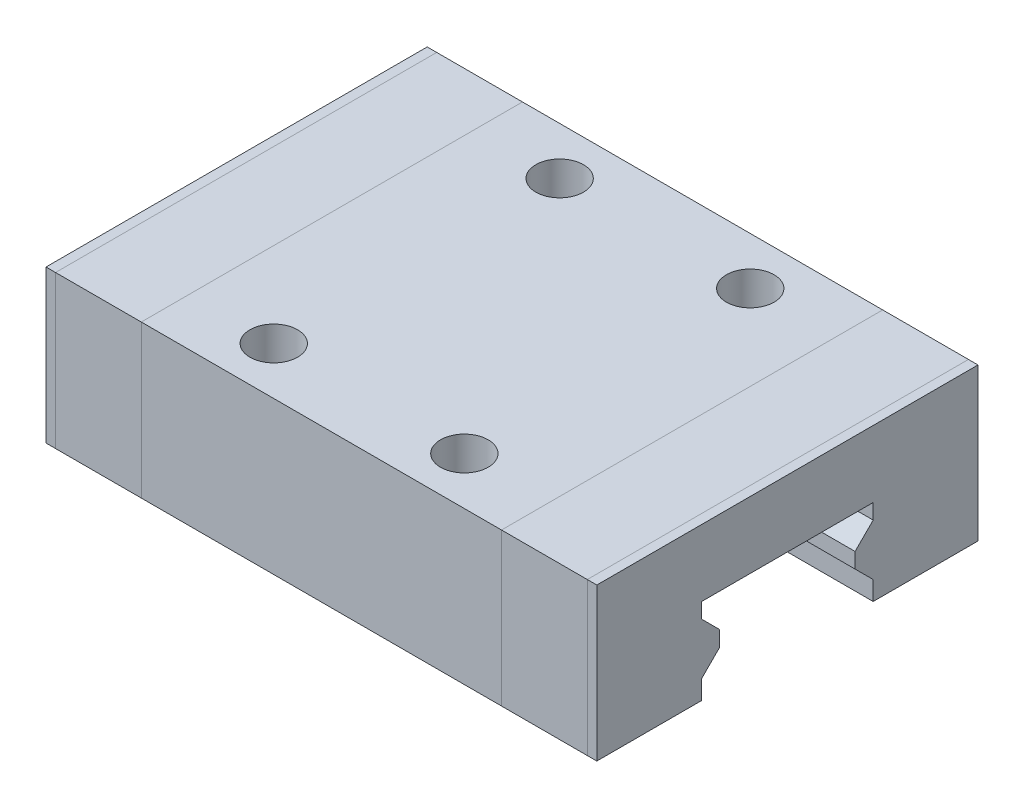
SolidWorks part; units mm, degrees
material "AISI 类型 316L 不锈钢"
ref_plane "前视" through (0, 0, 0) normal (0, 0, 1) x (1, 0, 0)
ref_plane "上视" through (0, 0, 0) normal (0, 1, 0) x (1, 0, 0)
ref_plane "右视" through (0, 0, 0) normal (1, 0, 0) x (0, 0, -1)
sketch "草图1" plane through (0, 0, 0) normal (0, 1, 0) x (1, 0, 0)
  line L1 (14.45, -10) -> (-14.45, -10)
  line L2 (14.45, -10) -> (14.45, 10)
  line L3 (14.45, 10) -> (-14.45, 10)
  line L4 (-14.45, -10) -> (-14.45, 10)
  line L5 (14.45, -10) -> (-14.45, 10) construction
  line L6 (14.45, 10) -> (-14.45, -10) construction
  point P0 (0, 0)
  dimension "D1" = 28.9
  dimension "D2" = 20
extrude "凸台-拉伸1" add sketch "草图1" along normal blind 8
sketch "草图3" plane through (0, 8, 0) normal (0, 1, 0) x (1, 0, 0)
  line L0 (-9.45, 10) -> (-9.45, -10)
  line L1 (14.45, 10) -> (-14.45, 10) construction
  line L2 (-14.45, -10) -> (14.45, -10) construction
  line L3 (9.45, -10) -> (9.45, 10)
  line L4 (0, 0) -> (0, 5.4273) construction
  line L5 (-13.95, 10) -> (-13.95, -10)
  line L6 (13.95, 10) -> (13.95, -10)
  line L7 (-14.45, 10) -> (-14.45, -10) construction
  dimension "D1" = 18.9
  dimension "D2" = 0.5
split line "分割线1"
sketch "草图2" plane through (-14.45, 0, 0) normal (-1, 0, 0) x (0, 0, 1)
  line L0 (-10, 8) -> (10, 8) construction
  line L17 (0, 0) -> (0, 4.5) construction
  line L18 (-4.5, 0) -> (-4.5, 1)
  line L19 (-4.5, 1) -> (-3.55, 1.95)
  line L20 (-3.55, 2.75) -> (-4.5, 3.7)
  line L21 (-4.5, 3.7) -> (-4.5, 4.5)
  line L22 (-4.5, 4.5) -> (4.5, 4.5)
  line L23 (4.5, 3.7) -> (4.5, 4.5)
  line L24 (3.55, 2.75) -> (3.55, 1.95)
  line L25 (3.55, 2.75) -> (4.5, 3.7)
  line L26 (4.5, 0) -> (4.5, 1)
  line L27 (-4.5, 0) -> (4.5, 0)
  line L28 (-3.55, 2.75) -> (-3.55, 1.95)
  line L29 (4.5, 1) -> (3.55, 1.95)
  dimension "D1" = 7
  dimension "D2" = 3.5
  dimension "D6" = 9
  dimension "D7" = 0.8
  dimension "D8" = 0.8
extrude "切除-拉伸1" cut sketch "草图2" against normal through all
sketch "草图4" plane through (0, 8, 0) normal (0, 1, 0) x (1, 0, 0)
  line L1 (5, -7.5) -> (-5, -7.5) construction
  line L2 (5, -7.5) -> (5, 7.5) construction
  line L3 (5, 7.5) -> (-5, 7.5) construction
  line L4 (-5, -7.5) -> (-5, 7.5) construction
  line L5 (5, -7.5) -> (-5, 7.5) construction
  line L6 (5, 7.5) -> (-5, -7.5) construction
  point P0 (0, 0)
  dimension "D1" = 10
  dimension "D2" = 15
hole_wizard "M3 螺纹孔1" positions "草图6" profile "草图5" tap size "M3" standard "Gb"
sketch "草图6" plane through (0, 8, 0) normal (0, 1, 0) x (1, 0, 0)
  point P0 (-5, -7.5)
  point P3 (5, -7.5)
  point P6 (5, 7.5)
  point P9 (-5, 7.5)
sketch "草图5" plane through (-5, 8, 7.5) normal (1, 0, 0) x (0, 0, 1)
  line L0 (0, 0) -> (0, 3.7511)
  line L1 (0, 3.7511) -> (1.25, 3)
  line L2 (1.25, 3) -> (1.25, 0)
  line L5 (1.25, 0) -> (0, 0)
  line L10 (0, 3.7511) -> (-1.25, 3) construction
  line L11 (0, -6.35) -> (0, 107.95) construction
  dimension "螺纹孔钻头直径" = 2.5
  dimension "螺纹孔钻头深度" = 3
  dimension "导头角度" = 118
cosmetic thread "孔螺蚊线1" parameters "D1"=3, "D2"=3
cosmetic thread "孔螺蚊线2" parameters "D1"=3, "D2"=3
cosmetic thread "孔螺蚊线3" parameters "D1"=3, "D2"=3
cosmetic thread "孔螺蚊线4" parameters "D1"=3, "D2"=3
